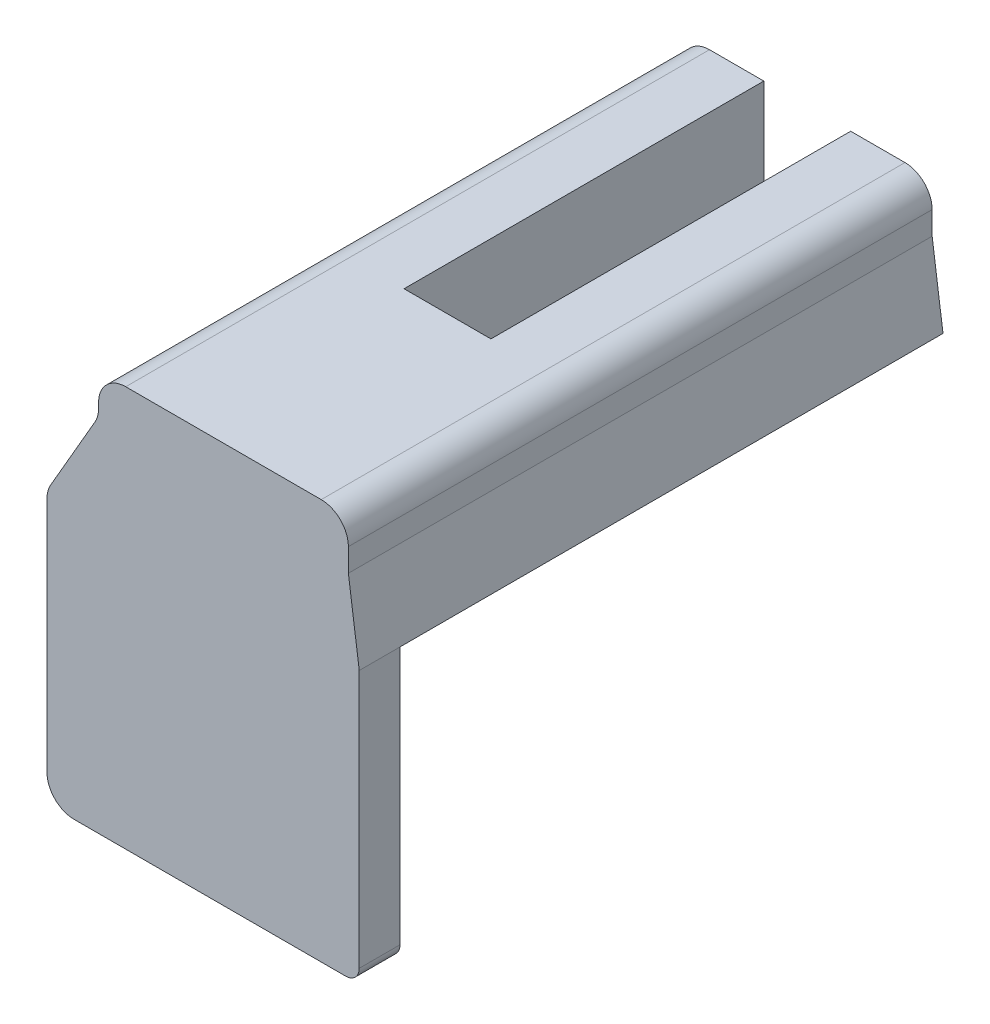
SolidWorks part; units mm, degrees
ref_plane "正面" through (0, 0, 0) normal (0, 0, 1) x (1, 0, 0)
ref_plane "平面" through (0, 0, 0) normal (0, 1, 0) x (1, 0, 0)
ref_plane "右側面" through (0, 0, 0) normal (1, 0, 0) x (0, 0, -1)
sketch "ｽｹｯﾁ1" plane through (0, 0, 0) normal (0, 0, 1) x (1, 0, 0)
  line L1 (-10, 10) -> (10, 10)
  line L2 (-10, 10) -> (-10, -10)
  line L3 (-10, -10) -> (10, -10)
  line L4 (10, 10) -> (10, -10)
  line L5 (-10, 10) -> (10, -10) construction
  line L6 (-10, -10) -> (10, 10) construction
  point P0 (0, 0)
  dimension "D1" = 20
extrude "ﾎﾞｽ - 押し出し1" add sketch "ｽｹｯﾁ1" along normal blind 3
sketch "ｽｹｯﾁ2" plane through (0, 0, 0) normal (0, 0, -1) x (-1, 0, 0)
  line L0 (-10, 10) -> (10, 10) construction
  line L1 (-3.5, 4) -> (3.5, 4)
  line L2 (-3.5, 4) -> (-3.5, 10)
  line L3 (-3.5, 10) -> (3.5, 10)
  line L4 (3.5, 4) -> (3.5, 10)
  line L5 (-3.5, 4) -> (3.5, 10) construction
  line L6 (-3.5, 10) -> (3.5, 4) construction
  line L7 (0, 0) -> (0, 7) construction
  point P0 (0, 7)
  dimension "D1" = 6
  dimension "D2" = 7
extrude "ﾎﾞｽ - 押し出し2" add sketch "ｽｹｯﾁ2" along normal blind 40
sketch "ｽｹｯﾁ3" plane through (0, 0, 3) normal (0, 0, 1) x (1, 0, 0)
  line L5 (-10, -10) -> (10, -10) construction
  line L6 (-10, 10) -> (-13, 10)
  line L7 (-10, 10) -> (-10, -10)
  line L8 (-10, -10) -> (-13, -10)
  line L9 (-13, 10) -> (-13, -10)
  dimension "D1" = 3
extrude "ﾎﾞｽ - 押し出し3" add sketch "ｽｹｯﾁ3" against normal blind 25
sketch "ｽｹｯﾁ4" plane through (-13, 0, 0) normal (1, 0, 0) x (0, 0, -1)
  line L0 (0, 0) -> (22, 0) construction
  circle A0 centre (10, 0) radius 2.6
  point P7 (0, 0)
  dimension "D1" = 10
  dimension "D2" = 5.2
extrude "ｶｯﾄ - 押し出し1" cut sketch "ｽｹｯﾁ4" along normal up to next
fillet "ﾌｨﾚｯﾄ1" radius 1 1 edges at (10, -10, 1.5)
ref_plane "平面1" through (0, 0, -13.5) normal (0, 0, -1) x (-1, 0, 0)
sketch "ｽｹｯﾁ5" plane through (0, 0, -13.5) normal (0, 0, -1) x (-1, 0, 0)
  line L0 (3.5, 10) -> (-3.5, 10) construction
  line L1 (-1.6, 6.1) -> (1.6, 6.1)
  line L2 (-1.6, 6.1) -> (-1.6, 10)
  line L3 (-1.6, 10) -> (1.6, 10)
  line L4 (1.6, 6.1) -> (1.6, 10)
  line L5 (-1.6, 6.1) -> (1.6, 10) construction
  line L6 (-1.6, 10) -> (1.6, 6.1) construction
  line L7 (0, 8.05) -> (0, 0) construction
  point P0 (0, 8.05)
  dimension "D1" = 3.2
  dimension "D2" = 3.9
extrude "ｶｯﾄ - 押し出し2" cut sketch "ｽｹｯﾁ5" along normal blind 30
sketch "ｽｹｯﾁ6" plane through (0, 0, 3) normal (0, 0, 1) x (1, 0, 0)
  line L0 (10, 10) -> (-13, 10) construction
  line L1 (3.2, 10) -> (9.2, 10)
  line L2 (3.2, 10) -> (3.2, 19.5)
  line L3 (3.2, 19.5) -> (9.2, 19.5)
  line L4 (9.2, 10) -> (9.2, 19.5)
  line L5 (0, 0) -> (0, 10) construction
  line L6 (-3.2, 19.5) -> (-9.2, 19.5)
  line L7 (-9.2, 10) -> (-9.2, 19.5)
  line L8 (-3.2, 10) -> (-9.2, 10)
  line L9 (-3.2, 10) -> (-3.2, 19.5)
  dimension "D1" = 6.4
  dimension "D2" = 9.5
  dimension "D3" = 6
extrude "ﾎﾞｽ - 押し出し4" add sketch "ｽｹｯﾁ6" against normal up to surface (43 mm away) up to face at (0, 7.525, -40)
chamfer "面取り1" distance 0.5 angle 45 2 edges at (-3.5, 10, -20) (3.5, 10, -20)
sketch "ｽｹｯﾁ7" plane through (0, 0, 3) normal (0, 0, 1) x (1, 0, 0)
  line L1 (-3.2, 19.5) -> (3.2, 19.5)
  line L2 (-3.2, 19.5) -> (-3.2, 10)
  line L3 (-3.2, 10) -> (3.2, 10)
  line L4 (3.2, 19.5) -> (3.2, 10)
extrude "ﾎﾞｽ - 押し出し5" add sketch "ｽｹｯﾁ7" against normal blind 16.5
sketch "ｽｹｯﾁ8" plane through (0, 0, 3) normal (0, 0, 1) x (1, 0, 0)
  line L4 (-13, 10) -> (-9.2, 10)
  line L5 (-9.2, 10) -> (-9.2, 16.5818)
  line L6 (-9.2, 19.5) -> (-9.2, 10) construction
  line L7 (-9.2, 16.5818) -> (-13, 10)
  dimension "D1" = 60
extrude "ﾎﾞｽ - 押し出し6" add sketch "ｽｹｯﾁ8" against normal up to surface (25 mm away) up to face at (-11.5, 0, -22)
fillet "ﾌｨﾚｯﾄ2" radius 2 5 edges at (9.2, 19.5, -18.5) (-9.2, 19.5, -18.5) (-13, -10, -9.5) (-13, 10, -9.5) (-9.2, 16.5818, -9.5)
sketch "ｽｹｯﾁ10" plane through (0, 0, -40) normal (0, 0, -1) x (-1, 0, 0)
  line L0 (3.5, 4) -> (3.5, 9.5) construction
  line L1 (1.6, 6.1) -> (3.5, 6.1)
  line L2 (1.6, 6.1) -> (1.6, 8.1)
  line L3 (1.6, 8.1) -> (3.5, 8.1)
  line L4 (3.5, 6.1) -> (3.5, 8.1)
  dimension "D1" = 2
extrude "ｶｯﾄ - 押し出し3" cut sketch "ｽｹｯﾁ10" against normal up to surface (26.5 mm away) up to face at (0, 11.4, -13.5)
fillet "ﾌｨﾚｯﾄ3" radius 0.5 2 edges at (-3.5, 8.1, -26.75) (-3.5, 6.1, -26.75)
fillet "ﾌｨﾚｯﾄ4" radius 1 2 edges at (3.5, 4, -20) (-3.5, 4, -20)
sketch "ｽｹｯﾁ9" plane through (0, 0, 3) normal (0, 0, 1) x (1, 0, 0)
  line L4 (10, 10) -> (9.2, 10)
  line L5 (9.2, 10) -> (9.2, 15.8)
  line L6 (9.2, 10) -> (9.2, 17.5) construction
  line L7 (9.2, 15.8) -> (10, 10)
  dimension "D1" = 5.8
extrude "ﾎﾞｽ - 押し出し7" add sketch "ｽｹｯﾁ9" against normal up to surface (43 mm away) up to face at (2.434, 9.4602, -40)
